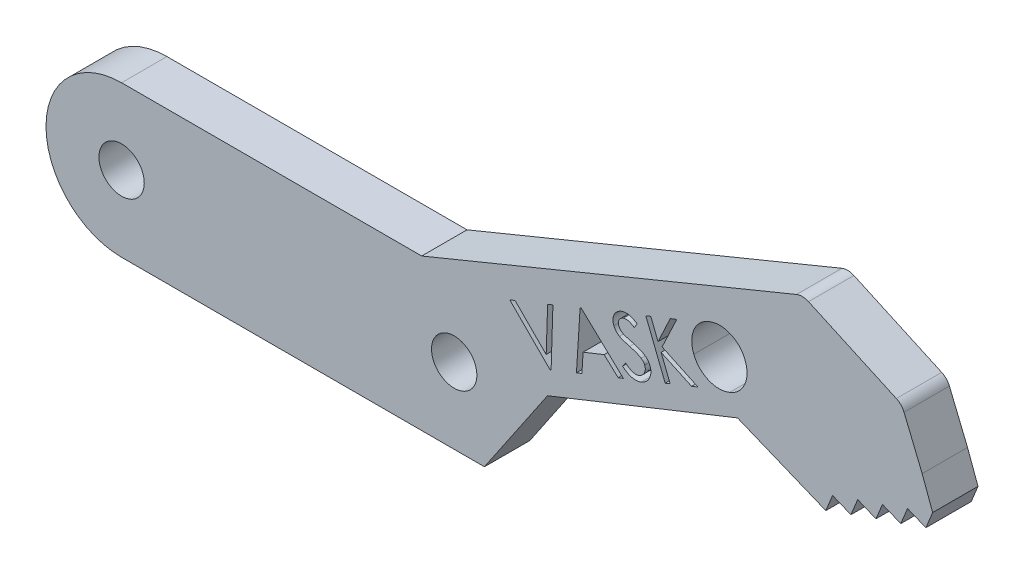
SolidWorks part; units mm, degrees
ref_plane "Front Plane" through (0, 0, 0) normal (0, 0, 1) x (1, 0, 0)
ref_plane "Top Plane" through (0, 0, 0) normal (0, 1, 0) x (1, 0, 0)
ref_plane "Right Plane" through (0, 0, 0) normal (1, 0, 0) x (0, 0, -1)
sketch "Sketch1" plane through (0, 0, 0) normal (0, 0, 1) x (1, 0, 0)
  line L0 (0, 0) -> (22, 0) construction
  line L1 (0, 5) -> (19.85, 5)
  line L2 (0, -5) -> (22, -5)
  line L3 (19.85, 5) -> (44.6431, 15.1937)
  line L4 (45.4379, 15.1788) -> (51.2451, 12.5335)
  line L5 (51.7554, 12.0038) -> (52.955, 9.0863)
  line L6 (24, -5) -> (22, -5)
  line L7 (24, -5) -> (28.1744, 1.1586)
  line L8 (28.1744, 1.1586) -> (40.742, 6.17)
  line L9 (40.742, 6.17) -> (46.5818, 3.7797)
  line L10 (46.5818, 3.7797) -> (47.0288, 4.8718)
  line L11 (47.0288, 4.8718) -> (48.2418, 4.3753)
  line L12 (48.2418, 4.3753) -> (48.6888, 5.4674)
  line L13 (48.6888, 5.4674) -> (49.9018, 4.9709)
  line L14 (49.9018, 4.9709) -> (50.3274, 6.0107)
  line L15 (50.3274, 6.0107) -> (51.5404, 5.5142)
  line L16 (51.5404, 5.5142) -> (51.9874, 6.6063)
  line L17 (51.9874, 6.6063) -> (53.2004, 6.1098)
  line L18 (53.2004, 6.1098) -> (53.6474, 7.2018)
  line L19 (53.6474, 7.2018) -> (52.955, 9.0863)
  arc A0 (0, 5) -> (0, -5) centre (0, 0) ccw
  circle A2 centre (0, 0) radius 1.5
  circle A3 centre (22, 0) radius 1.5
  arc A4 (51.2451, 12.5335) -> (51.7554, 12.0038) centre (50.8306, 11.6235) cw
  arc A5 (44.6431, 15.1937) -> (45.4379, 15.1788) centre (45.0233, 14.2688) cw
  point P3 (11, 0)
  point P18 (51.605, 12.3696)
  point P21 (45.0437, 15.3584)
  point P22 (24, -5)
  point P37 (25.5235, 2.3158)
  point P38 (0, 0)
  point P39 (0, 0)
  point P40 (37.0314, 7.2018)
  point P41 (37.5297, 7.2018)
  point P42 (27.0189, 1.9096)
  point P43 (26.4752, 1.6831)
  point P44 (25.9768, 1.7284)
  point P45 (0, 0)
  point P46 (0, 0)
  point P47 (25.4332, 1.8643)
  dimension "D3" = 3
  dimension "D4" = 3
  dimension "D12" = 1
  dimension "D2" = 5
  dimension "D5" = 19.85
  dimension "D6" = 157.65
  dimension "D7" = 27.24
  dimension "D8" = 133.16
  dimension "D9" = 7.21
  dimension "D10" = 136.84
  dimension "D11" = 3.55
  dimension "D13" = 24
  dimension "D14" = 55.87
  dimension "D15" = 7.44
  dimension "D16" = 214.13
  dimension "D17" = 13.53
  dimension "D18" = 224
  dimension "D19" = 6.31
  dimension "D20" = 1.18
  dimension "D21" = 1.66
  dimension "D22" = 2.0076
  dimension "D23" = 10
  dimension "D24" = 22
extrude "Boss-Extrude1" add sketch "Sketch1" along normal blind 3 contours A5 L3 L1 A0 L2 L6 L7 L8 L9 L10 L11 L12 L13 L14 L15 L16 L17 L18 L19 L5 A4 L4 A3 A2
sketch "Sketch2" plane through (0, 0, 3) normal (0, 0, 1) x (1, 0, 0)
  line L0 (26.8121, 2.1203) -> (39.3798, 7.1318) construction
  line L1 (28.1744, 1.1586) -> (40.742, 6.17) construction
  text T0 "VASKO"
  point P5 (30.4403, 5.1639)
  point P6 (30.5478, 5.2027)
  point P7 (31.4307, 4.5095)
extrude "Cut-Extrude2" cut sketch "Sketch2" against normal blind 10
